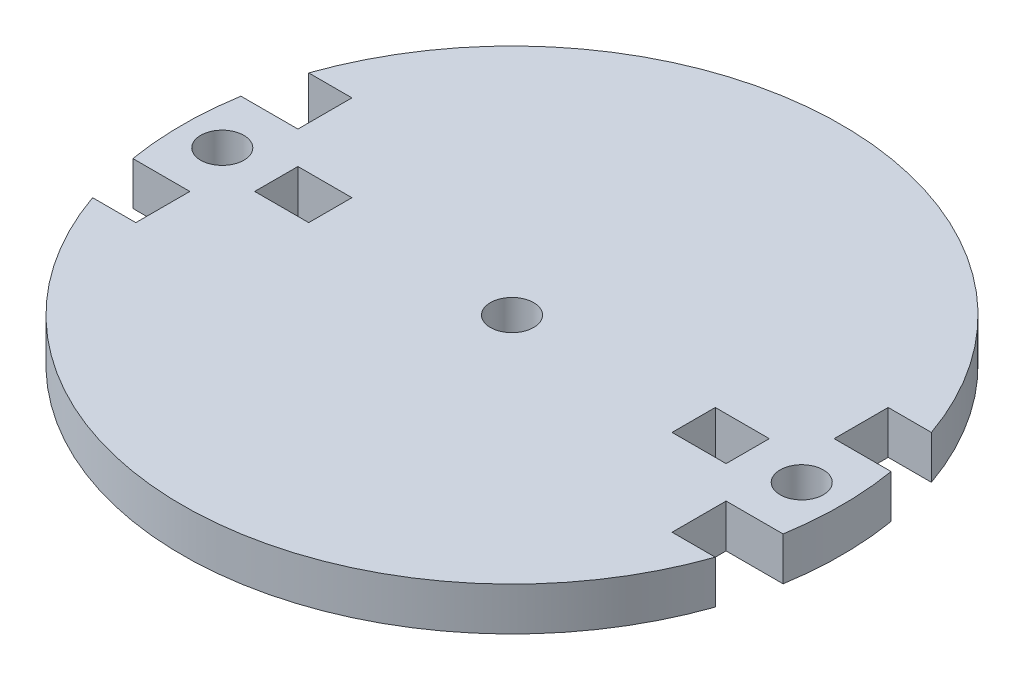
SolidWorks part; units mm, degrees
ref_plane "Alzado" through (0, 0, 0) normal (0, 0, 1) x (1, 0, 0)
ref_plane "Planta" through (0, 0, 0) normal (0, 1, 0) x (1, 0, 0)
ref_plane "Vista lateral" through (0, 0, 0) normal (1, 0, 0) x (0, 0, -1)
sketch "Croquis1" plane through (0, 0, 0) normal (0, 1, 0) x (1, 0, 0)
  circle A0 centre (0, 0) radius 30.5
extrude "Saliente-Extruir1" add sketch "Croquis1" along normal blind 4
sketch "Croquis2" plane through (0, 4, 0) normal (0, 1, 0) x (1, 0, 0)
  circle A0 centre (0, 0) radius 2
extrude "Cortar-Extruir1" cut sketch "Croquis2" against normal blind 4
sketch "Croquis5" plane through (0, 4, 0) normal (0, 1, 0) x (1, 0, 0)
  line L0 (0, 0) -> (0, 10)
  line L1 (28.8141, -5) -> (30.0874, -5)
  line L2 (28.8141, 5) -> (30.0874, 5)
  line L3 (-24.8141, 10) -> (-28.8141, 10)
  line L4 (24.8141, -5) -> (24.8141, -10)
  line L5 (-24.8141, -10) -> (-28.8141, -10)
  line L6 (24.8141, -5) -> (28.8141, -5)
  line L7 (24.8141, 5) -> (24.8141, 10)
  line L8 (-24.8141, 5) -> (-28.8141, 5)
  line L9 (-24.8141, 5) -> (-24.8141, 10)
  line L10 (-24.8141, -5) -> (-28.8141, -5)
  line L11 (-24.8141, -5) -> (-24.8141, -10)
  line L12 (24.8141, 5) -> (28.8141, 5)
  line L13 (24.8141, -10) -> (28.8141, -10)
  line L14 (24.8141, 10) -> (28.8141, 10)
  line L15 (-28.8141, 5) -> (-30.0874, 5)
  line L16 (-28.8141, -5) -> (-30.0874, -5)
  circle A1 centre (0, 0) radius 30.5 construction
  arc A2 (-28.8141, 10) -> (-30.0874, 5) centre (0, 0) ccw
  arc A3 (28.8141, 10) -> (28.8141, -10) centre (0, 0) cw
  arc A4 (-30.0874, -5) -> (-28.8141, -10) centre (0, 0) ccw
  arc A5 (30.0874, -5) -> (28.8141, -10) centre (0, 0) cw
  arc A6 (28.8141, 10) -> (30.0874, 5) centre (0, 0) cw
extrude "Cortar-Extruir3" cut sketch "Croquis5" against normal blind 4
sketch "Croquis6" plane through (0, 4, 0) normal (0, 1, 0) x (1, 0, 0)
  line L8 (-21.8141, 2) -> (-21.8141, -2)
  line L9 (16.8141, 2) -> (21.8141, 2)
  line L10 (16.8141, -2) -> (16.8141, 2)
  line L11 (16.8141, -2) -> (21.8141, -2)
  line L12 (-16.8141, -2) -> (-21.8141, -2)
  line L13 (21.8141, 2) -> (21.8141, -2)
  line L14 (-16.8141, -2) -> (-16.8141, 2)
  line L15 (-16.8141, 2) -> (-21.8141, 2)
extrude "Cortar-Extruir4" cut sketch "Croquis6" against normal blind 4
sketch "Croquis7" plane through (0, 4, 0) normal (0, 1, 0) x (1, 0, 0)
  circle A1 centre (-26.8141, 0) radius 2
  circle A2 centre (26.8141, 0) radius 2
extrude "Cortar-Extruir5" cut sketch "Croquis7" against normal blind 4
